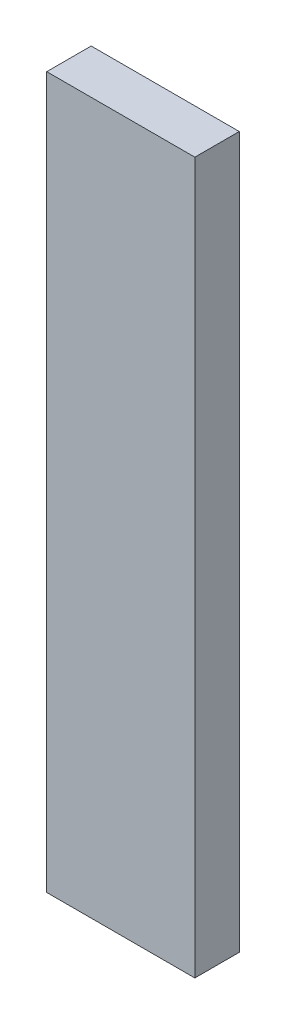
SolidWorks part; units mm, degrees
ref_plane "Front Plane" through (0, 0, 0) normal (0, 0, 1) x (1, 0, 0)
ref_plane "Top Plane" through (0, 0, 0) normal (0, 1, 0) x (1, 0, 0)
ref_plane "Right Plane" through (0, 0, 0) normal (1, 0, 0) x (0, 0, -1)
sketch "Sketch1" plane through (0, 0, 0) normal (0, 1, 0) x (1, 0, 0)
  line L1 (0, 0) -> (63.5, 0)
  line L2 (0, 0) -> (0, 19.05)
  line L3 (0, 19.05) -> (63.5, 19.05)
  line L4 (63.5, 0) -> (63.5, 19.05)
  dimension "D1" = 19.05
  dimension "D2" = 63.5
extrude "Boss-Extrude1" add sketch "Sketch1" along normal blind 304.8
